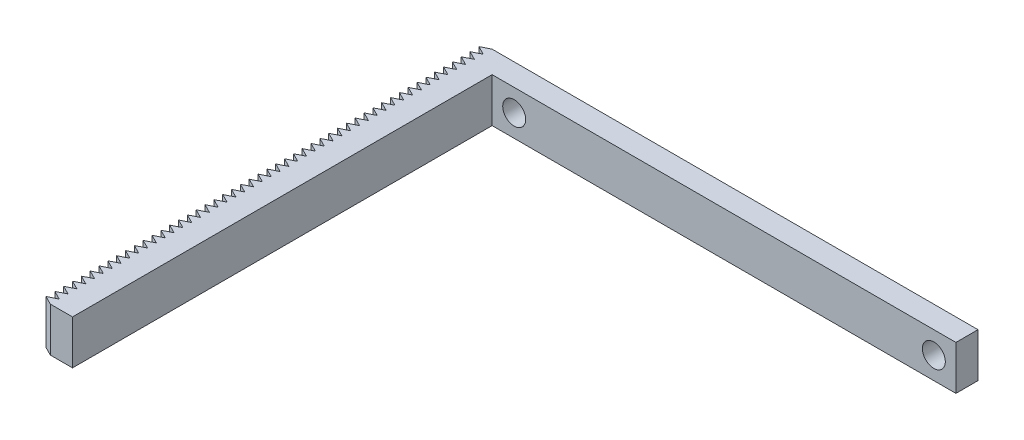
SolidWorks part; units mm, degrees
ref_plane "Front Plane" through (0, 0, 0) normal (0, 0, 1) x (1, 0, 0)
ref_plane "Top Plane" through (0, 0, 0) normal (0, 1, 0) x (1, 0, 0)
ref_plane "Right Plane" through (0, 0, 0) normal (1, 0, 0) x (0, 0, -1)
sketch "Sketch1" plane through (0, 0, 0) normal (0, 0, 1) x (1, 0, 0)
  line L0 (0, 0) -> (0, 29.4443) construction
  line L1 (-66.675, -6.35) -> (66.675, -6.35)
  line L2 (-66.675, -6.35) -> (-66.675, 6.35)
  line L3 (-66.675, 6.35) -> (66.675, 6.35)
  line L4 (66.675, -6.35) -> (66.675, 6.35)
  line L5 (-66.675, -6.35) -> (66.675, 6.35) construction
  line L6 (-66.675, 6.35) -> (66.675, -6.35) construction
  circle A0 centre (-60.325, 0) radius 3.302
  circle A2 centre (60.325, 0) radius 3.302
  point P0 (0, 0)
  dimension "D5" = 6.604
  dimension "D1" = 12.7
  dimension "D3" = 6.35
  dimension "D4" = 6.35
  dimension "D2" = 120.65
extrude "Boss-Extrude1" add sketch "Sketch1" along normal mid plane 6.35
sketch "Sketch2" plane through (0, 0, 0) normal (0, 0, 1) x (1, 0, 0)
  line L0 (-66.675, -6.35) -> (66.675, -6.35) construction
  line L1 (-66.675, 6.35) -> (-73.025, 6.35)
  line L2 (-66.675, 6.35) -> (-66.675, -6.35)
  line L3 (-66.675, -6.35) -> (-73.025, -6.35)
  line L4 (-73.025, 6.35) -> (-73.025, -6.35)
  line L5 (66.675, 6.35) -> (-66.675, 6.35) construction
  line L6 (-66.675, 6.35) -> (-66.675, -6.35) construction
  dimension "D1" = 6.35
extrude "Boss-Extrude2" add sketch "Sketch2" along normal blind 127 from surface at -3.175 starting at face at (-57.023, 0, -3.175)
sketch "Sketch4" plane through (0, 6.35, 0) normal (0, 1, 0) x (1, 0, 0)
  line L0 (-73.025, 3.175) -> (-75.565, 1.905)
  line L1 (-75.565, 1.905) -> (-73.025, 0.635)
  line L2 (-73.025, -123.825) -> (-73.025, 3.175) construction
  line L3 (-73.025, 0.635) -> (-73.025, 3.175)
  dimension "D1" = 2.54
  dimension "D2" = 1.27
  dimension "D3" = 1.27
extrude "Boss-Extrude3" add sketch "Sketch4" against normal up to surface (12.7 mm away) up to face at (-24.3417, -6.35, 41.275)
pattern_linear "LPattern1" count 50 spacing 2.54 along (0, 0, 1) of "Boss-Extrude3"
equation "\"tightTol\" = 0.005in"
equation "\"normTol\"= 0.01in"
equation "\"looseTol\"= 0.02in"
equation "\"D5@Sketch1\"=\"normTol\"+0.250000in"
